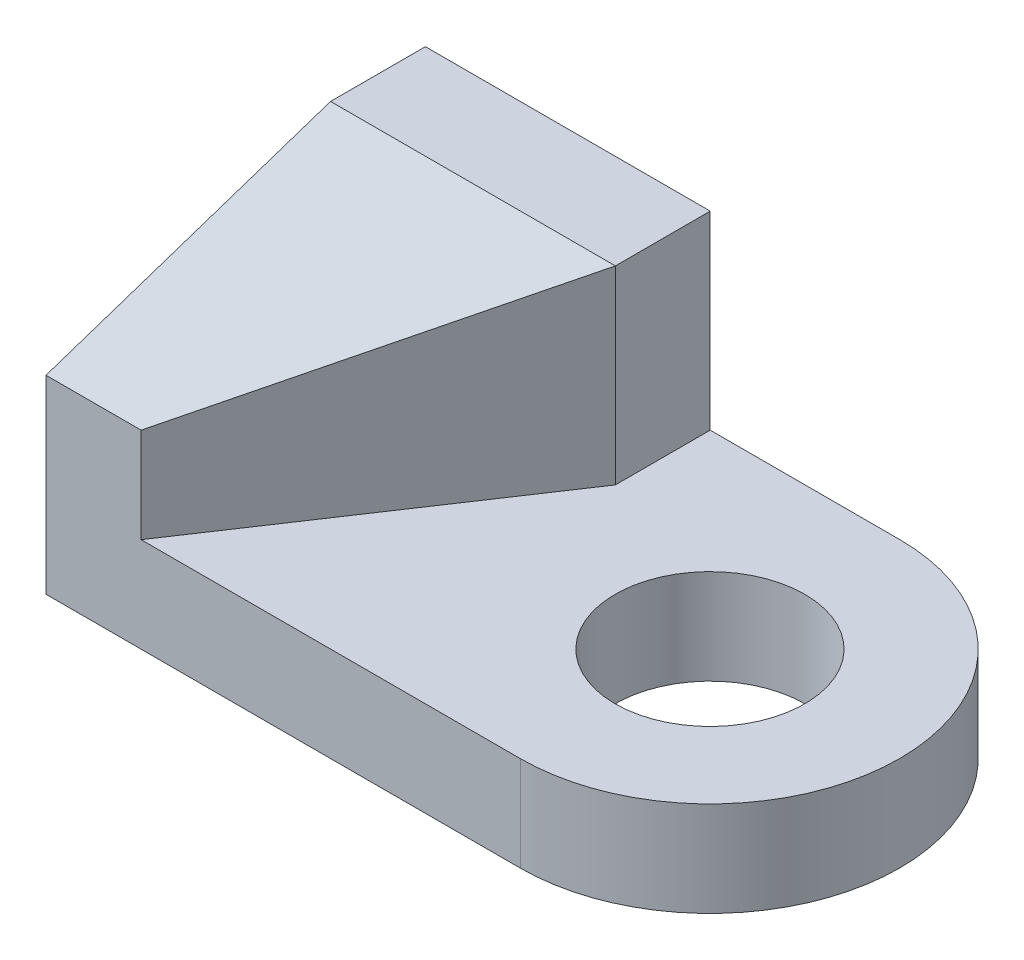
SolidWorks part; units mm, degrees
ref_plane "Front Plane" through (0, 0, 0) normal (0, 0, 1) x (1, 0, 0)
ref_plane "Top Plane" through (0, 0, 0) normal (0, 1, 0) x (1, 0, 0)
ref_plane "Right Plane" through (0, 0, 0) normal (1, 0, 0) x (0, 0, -1)
sketch "Sketch1" plane through (0, 0, 0) normal (0, 1, 0) x (1, 0, 0)
  line L0 (0, 20) -> (-50, 20)
  line L1 (-50, 20) -> (-50, -20)
  line L2 (-50, -20) -> (0, -20)
  circle A0 centre (0, 0) radius 10
  arc A1 (0, -20) -> (0, 20) centre (0, 0) ccw
  dimension "D1" = 20
  dimension "D2" = 40
  dimension "D3" = 50
extrude "Boss-Extrude1" add sketch "Sketch1" along normal blind 10
sketch "Sketch2" plane through (0, 10, 0) normal (0, 1, 0) x (1, 0, 0)
  line L0 (-50, 20) -> (-19.9711, 20)
  line L1 (0, 20) -> (-50, 20) construction
  line L2 (-19.9711, 20) -> (-19.9711, -20)
  line L3 (-50, -20) -> (0, -20) construction
  line L4 (-19.9711, -20) -> (-50, -20)
  line L5 (-50, -20) -> (-50, 20)
extrude "Boss-Extrude2" add sketch "Sketch2" along normal blind 20 contours L2 L4 L5 L0
sketch "Sketch3" plane through (-19.9711, 0, 0) normal (1, 0, 0) x (0, 0, -1)
  line L0 (20, 30) -> (10, 30)
  line L1 (20, 30) -> (-20, 30) construction
  line L2 (10, 30) -> (-20, 20)
  line L3 (-20, 30) -> (-20, 10) construction
  line L4 (-20, 20) -> (-20, 0)
  line L5 (-20, 0) -> (20, 0) construction
  line L6 (-20, 0) -> (20, 0)
  line L7 (20, 0) -> (20, 30)
  dimension "D1" = 10
  dimension "D2" = 10
extrude "Cut-Extrude1" cut sketch "Sketch3" against normal blind 36 flip side to cut
sketch "Sketch4" plane through (0, 30, 0) normal (0, 1, 0) x (1, 0, 0)
  line L3 (-19.9711, -20) -> (-19.9711, 10)
  line L4 (-19.9711, 10) -> (-39.9711, -20)
  line L5 (-50, -20) -> (-19.9711, -20) construction
  line L6 (-39.9711, -20) -> (-19.9711, -20)
  dimension "D1" = 20
extrude "Cut-Extrude2" cut sketch "Sketch4" along direction (0, 1, 0) on the side against the normal blind 20
